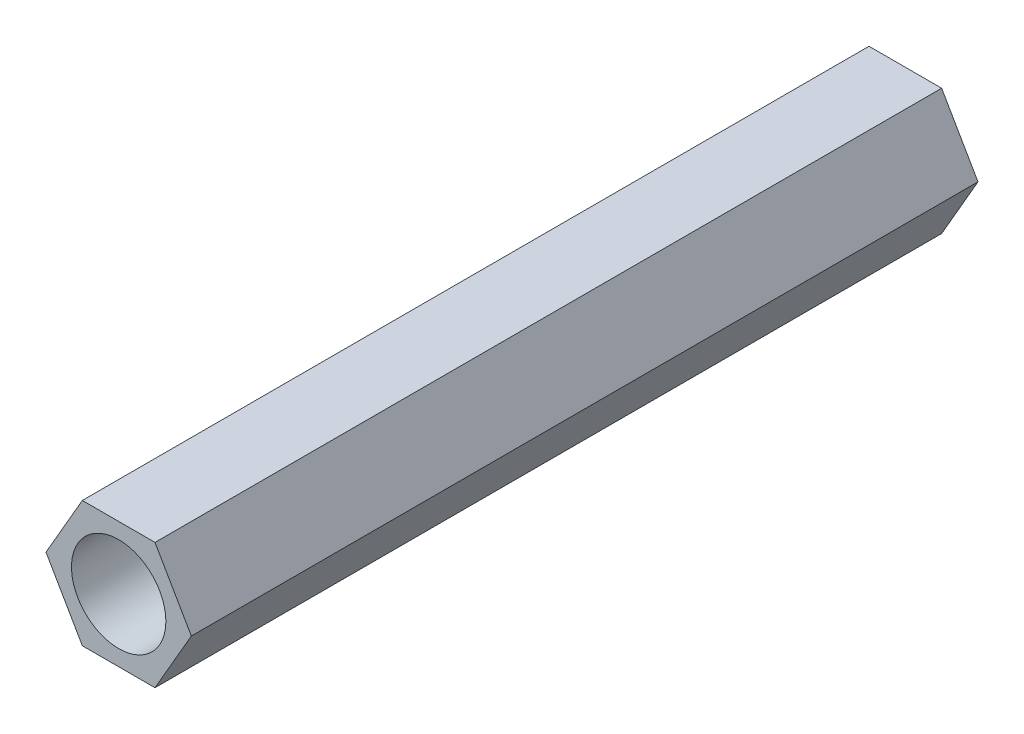
SolidWorks part; units mm, degrees
ref_plane "前视基准面" through (0, 0, 0) normal (0, 0, 1) x (1, 0, 0)
ref_plane "上视基准面" through (0, 0, 0) normal (0, 1, 0) x (1, 0, 0)
ref_plane "右视基准面" through (0, 0, 0) normal (1, 0, 0) x (0, 0, -1)
other "Configuration Table"
sketch "草图1" plane through (0, 0, 0) normal (0, 0, 1) x (1, 0, 0)
  line L1 (2.3094, 0) -> (1.1547, 2)
  line L2 (1.1547, 2) -> (-1.1547, 2)
  line L3 (-1.1547, 2) -> (-2.3094, 0)
  line L4 (-2.3094, 0) -> (-1.1547, -2)
  line L5 (-1.1547, -2) -> (1.1547, -2)
  line L6 (1.1547, -2) -> (2.3094, 0)
  circle A0 centre (0, 0) radius 2 construction
  circle A1 centre (0, 0) radius 1.5
  dimension "D1" = 2
extrude "凸台-拉伸1" add sketch "草图1" along normal blind 25
